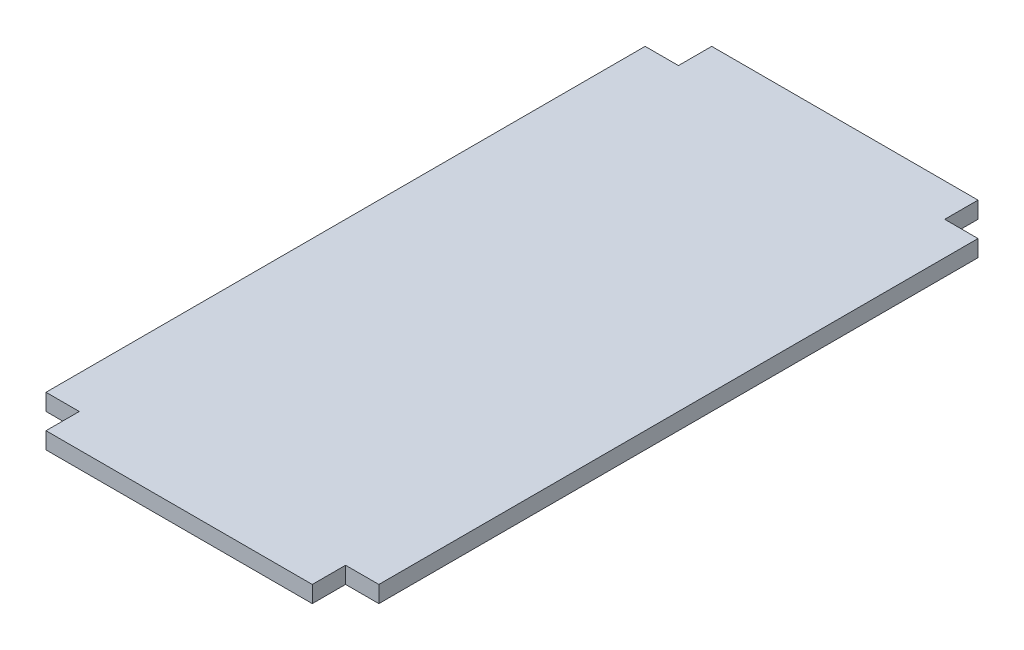
SolidWorks part; units mm, degrees
material "Oak"
ref_plane "Front Plane" through (0, 0, 0) normal (0, 0, 1) x (1, 0, 0)
ref_plane "Top Plane" through (0, 0, 0) normal (0, 1, 0) x (1, 0, 0)
ref_plane "Right Plane" through (0, 0, 0) normal (1, 0, 0) x (0, 0, -1)
sketch "Sketch1" plane through (0, 0, 0) normal (0, 1, 0) x (1, 0, 0)
  line L0 (-194.7505, -920.1839) -> (-194.7505, -234.3839)
  line L1 (-194.7505, -234.3839) -> (-156.6505, -234.3839)
  line L2 (-156.6505, -234.3839) -> (-156.6505, -196.2839)
  line L3 (-156.6505, -196.2839) -> (148.1495, -196.2839)
  line L4 (148.1495, -196.2839) -> (148.1495, -234.3839)
  line L5 (148.1495, -234.3839) -> (186.2495, -234.3839)
  line L6 (186.2495, -234.3839) -> (186.2495, -920.1839)
  line L7 (186.2495, -920.1839) -> (148.1495, -920.1839)
  line L8 (148.1495, -920.1839) -> (148.1495, -958.2839)
  line L9 (148.1495, -958.2839) -> (-156.6505, -958.2839)
  line L10 (-156.6505, -958.2839) -> (-156.6505, -920.1839)
  line L11 (-156.6505, -920.1839) -> (-194.7505, -920.1839)
  dimension "D1" = 762
  dimension "D2" = 304.8
  dimension "D3" = 304.8
  dimension "D4" = 38.1
  dimension "D5" = 38.1
  dimension "D6" = 38.1
  dimension "D7" = 685.8
  dimension "D8" = 38.1
  dimension "D9" = 685.8
  dimension "D10" = 38.1
extrude "Boss-Extrude1" add sketch "Sketch1" along normal blind 19.05
